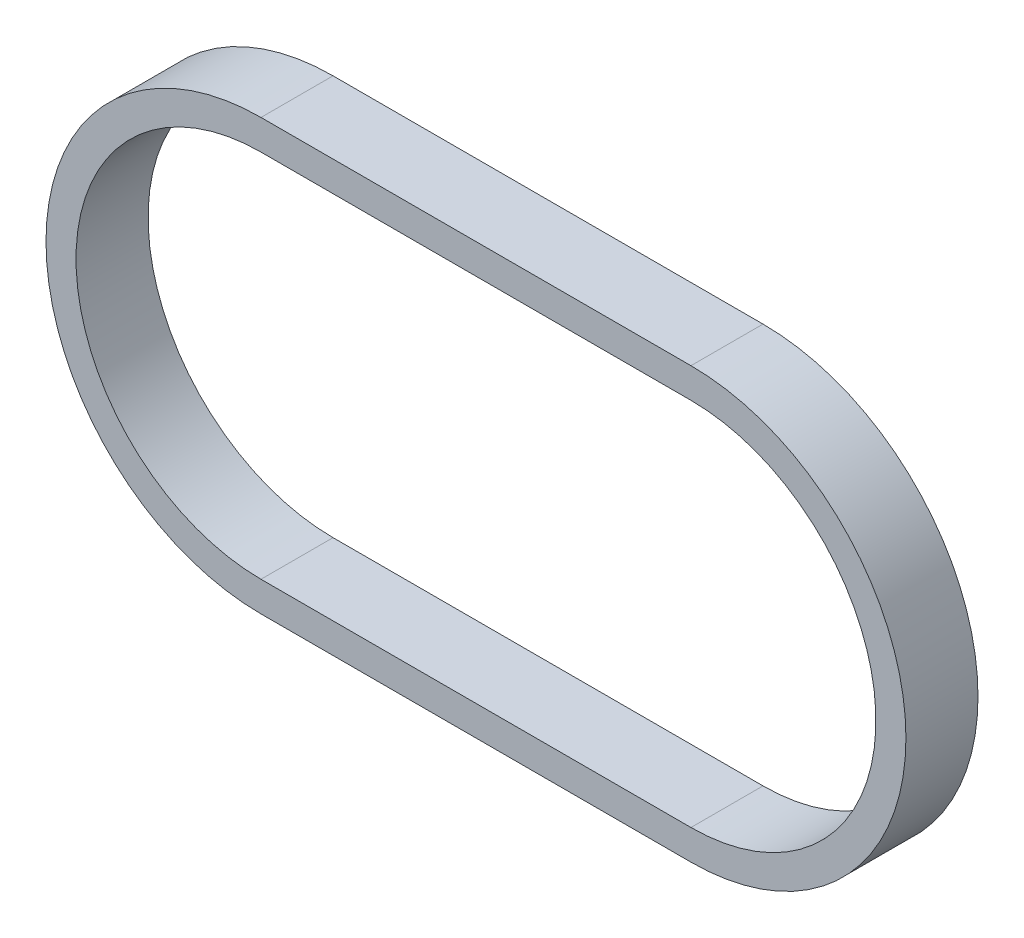
SolidWorks part; units mm, degrees
ref_plane "Plan de face" through (0, 0, 0) normal (0, 0, 1) x (1, 0, 0)
ref_plane "Plan de dessus" through (0, 0, 0) normal (0, 1, 0) x (1, 0, 0)
ref_plane "Plan de droite" through (0, 0, 0) normal (1, 0, 0) x (0, 0, -1)
sketch "Esquisse4" plane through (0, 0, 0) normal (0, 0, 1) x (1, 0, 0)
  line L0 (-17.9, -17.9) -> (17.9, -17.9)
  line L2 (17.9, -15.4) -> (-17.9, -15.4)
  line L4 (17.9, 17.9) -> (-17.9, 17.9)
  line L5 (-17.9, 15.4) -> (17.9, 15.4)
  arc A0 (17.9, -17.9) -> (17.9, 17.9) centre (17.9, 0) ccw
  arc A1 (17.9, 15.4) -> (17.9, -15.4) centre (17.9, 0) cw
  arc A2 (-17.9, -15.4) -> (-17.9, 15.4) centre (-17.9, 0) cw
  arc A3 (-17.9, 17.9) -> (-17.9, -17.9) centre (-17.9, 0) ccw
  point P18 (0, 0)
  dimension "D7" = 17.9
  dimension "D1" = 2.5
  dimension "D2" = 35.8
  dimension "D3" = 17.9
  dimension "D4" = 35.8
  dimension "D5" = 17.9
  dimension "D6" = 2
extrude "Boss.-Extru.2" add sketch "Esquisse4" along normal blind 6
